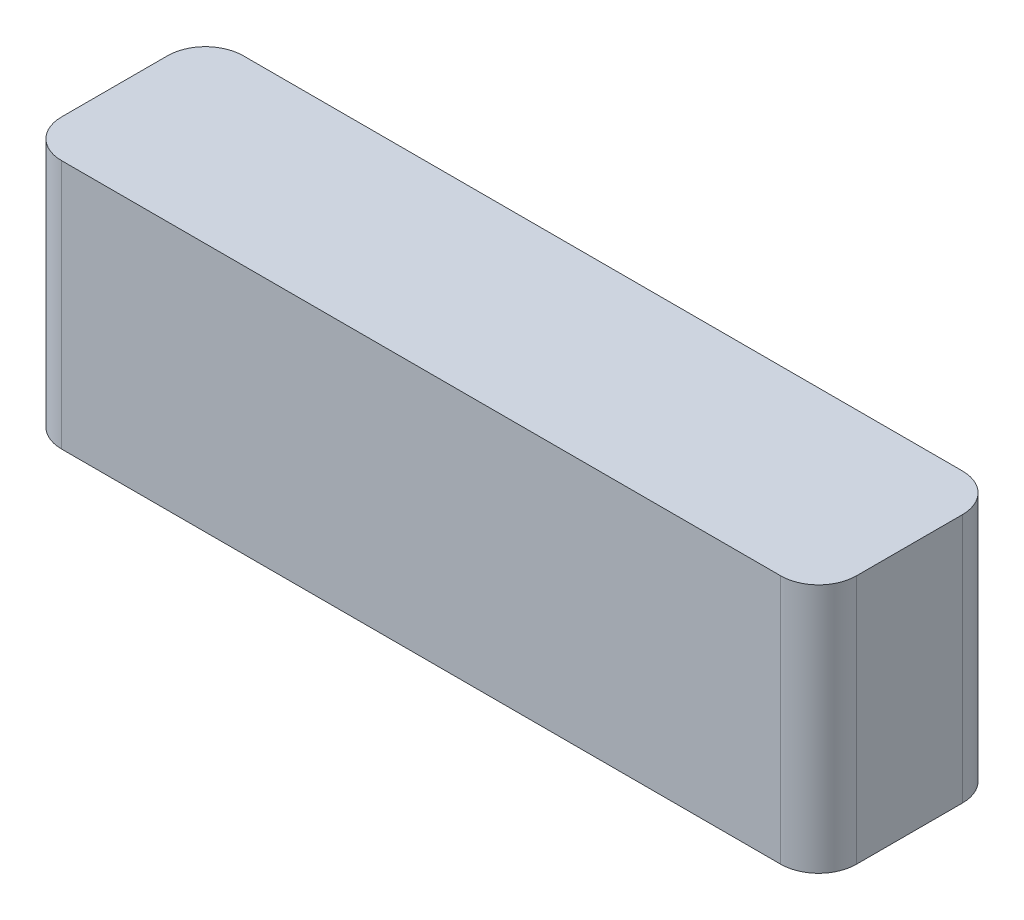
SolidWorks part; units mm, degrees
ref_plane "Front Plane" through (0, 0, 0) normal (0, 0, 1) x (1, 0, 0)
ref_plane "Top Plane" through (0, 0, 0) normal (0, 1, 0) x (1, 0, 0)
ref_plane "Right Plane" through (0, 0, 0) normal (1, 0, 0) x (0, 0, -1)
sketch "Sketch2" plane through (0, 0, 0) normal (0, 1, 0) x (1, 0, 0)
  line L1 (-52.5, -12) -> (52.5, -12)
  line L2 (-52.5, -12) -> (-52.5, 12)
  line L3 (-52.5, 12) -> (52.5, 12)
  line L4 (52.5, -12) -> (52.5, 12)
  line L5 (-52.5, -12) -> (52.5, 12) construction
  line L6 (-52.5, 12) -> (52.5, -12) construction
  point P0 (0, 0)
  dimension "D1" = 105
  dimension "D2" = 24
extrude "Boss-Extrude1" add sketch "Sketch2" along normal blind 33
fillet "Fillet1" radius 5 4 edges at (-52.5, 16.5, 12) (-52.5, 16.5, -12) (52.5, 16.5, -12) (52.5, 16.5, 12)
